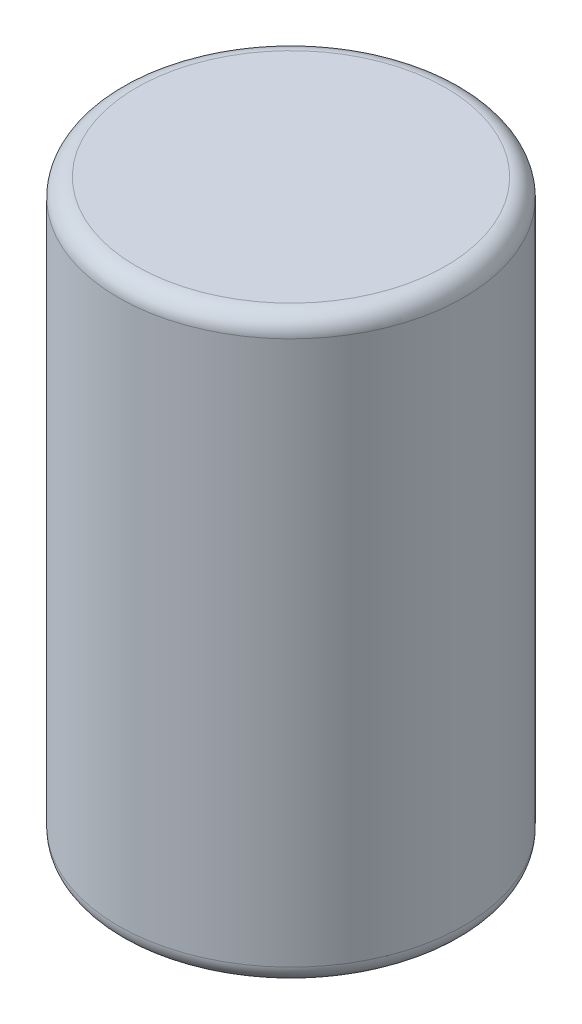
SolidWorks part; units mm, degrees
ref_plane "Front Plane" through (0, 0, 0) normal (0, 0, 1) x (1, 0, 0)
ref_plane "Top Plane" through (0, 0, 0) normal (0, 1, 0) x (1, 0, 0)
ref_plane "Right Plane" through (0, 0, 0) normal (1, 0, 0) x (0, 0, -1)
sketch "Sketch1" plane through (0, 0, 0) normal (0, 1, 0) x (1, 0, 0)
  circle A0 centre (0, 0) radius 4.7625
  dimension "D1" = 9.525
extrude "Boss-Extrude1" add sketch "Sketch1" along normal blind 16
fillet "Fillet2" radius 0.5 1 edges at (0, 16, 4.7625)
fillet "Fillet3" radius 0.5 1 edges at (0, 0, 4.7625)
